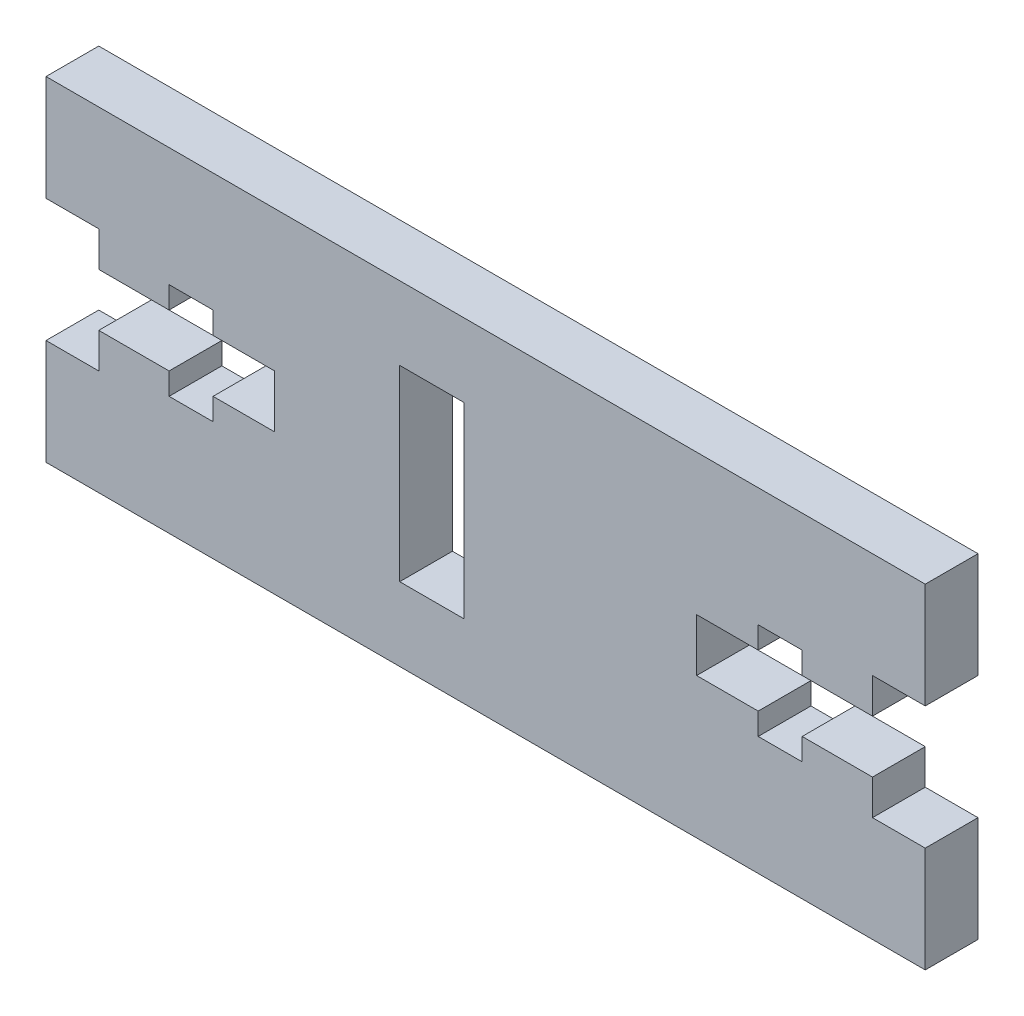
SolidWorks part; units mm, degrees
ref_plane "前视基准面" through (0, 0, 0) normal (0, 0, 1) x (1, 0, 0)
ref_plane "上视基准面" through (0, 0, 0) normal (0, 1, 0) x (1, 0, 0)
ref_plane "右视基准面" through (0, 0, 0) normal (1, 0, 0) x (0, 0, -1)
ref_plane "基准面4" through (0, 0, 3) normal (0, 0, 1) x (1, 0, 0)
sketch "草图1" plane through (0, 0, 3) normal (0, 0, 1) x (1, 0, 0)
  line L0 (45.58, 0) -> (45.58, 6)
  line L1 (45.58, 6) -> (42.58, 6)
  line L2 (42.58, 6) -> (42.58, 7.9995)
  line L3 (42.58, 7.9995) -> (38.581, 7.9995)
  line L4 (38.581, 7.9995) -> (38.581, 6.7496)
  line L5 (38.581, 6.7496) -> (36.0798, 6.7496)
  line L6 (36.0798, 6.7496) -> (36.0798, 7.9995)
  line L7 (36.0798, 7.9995) -> (32.58, 7.9995)
  line L8 (32.58, 7.9995) -> (32.58, 10.9995)
  line L9 (32.58, 10.9995) -> (36.0798, 10.9995)
  line L10 (36.0798, 10.9995) -> (36.0798, 12.2508)
  line L11 (36.0798, 12.2508) -> (38.581, 12.2508)
  line L12 (38.581, 12.2508) -> (38.581, 10.9995)
  line L13 (38.581, 10.9995) -> (42.58, 10.9995)
  line L14 (42.58, 10.9995) -> (42.58, 13.0004)
  line L15 (42.58, 13.0004) -> (45.58, 13.0004)
  line L16 (45.58, 13.0004) -> (45.58, 19.0004)
  line L17 (45.58, 19.0004) -> (-4.4194, 19.0004)
  line L18 (-4.4194, 19.0004) -> (-4.4194, 13.0004)
  line L19 (-4.4194, 13.0004) -> (-1.4194, 13.0004)
  line L20 (-1.4194, 13.0004) -> (-1.4194, 10.9995)
  line L21 (-1.4194, 10.9995) -> (2.5796, 10.9995)
  line L22 (2.5796, 10.9995) -> (2.5796, 12.2508)
  line L23 (2.5796, 12.2508) -> (5.0808, 12.2508)
  line L24 (5.0808, 12.2508) -> (5.0808, 10.9995)
  line L25 (5.0808, 10.9995) -> (8.5806, 10.9995)
  line L26 (8.5806, 10.9995) -> (8.5806, 7.9995)
  line L27 (8.5806, 7.9995) -> (5.0808, 7.9995)
  line L28 (5.0808, 7.9995) -> (5.0808, 6.7496)
  line L29 (5.0808, 6.7496) -> (2.5796, 6.7496)
  line L30 (2.5796, 6.7496) -> (2.5796, 7.9995)
  line L31 (2.5796, 7.9995) -> (-1.4194, 7.9995)
  line L32 (-1.4194, 7.9995) -> (-1.4194, 6)
  line L33 (-1.4194, 6) -> (-4.4194, 6)
  line L34 (-4.4194, 6) -> (-4.4194, 0)
  line L35 (-4.4194, 0) -> (45.58, 0)
  line L36 (15.6941, 14.8305) -> (19.3546, 14.8305)
  line L37 (19.3546, 14.8305) -> (19.3546, 4.1777)
  line L38 (19.3546, 4.1777) -> (15.6941, 4.1777)
  line L39 (15.6941, 4.1777) -> (15.6941, 14.8305)
extrude "凸台-拉伸1" add sketch "草图1" against normal blind 3
